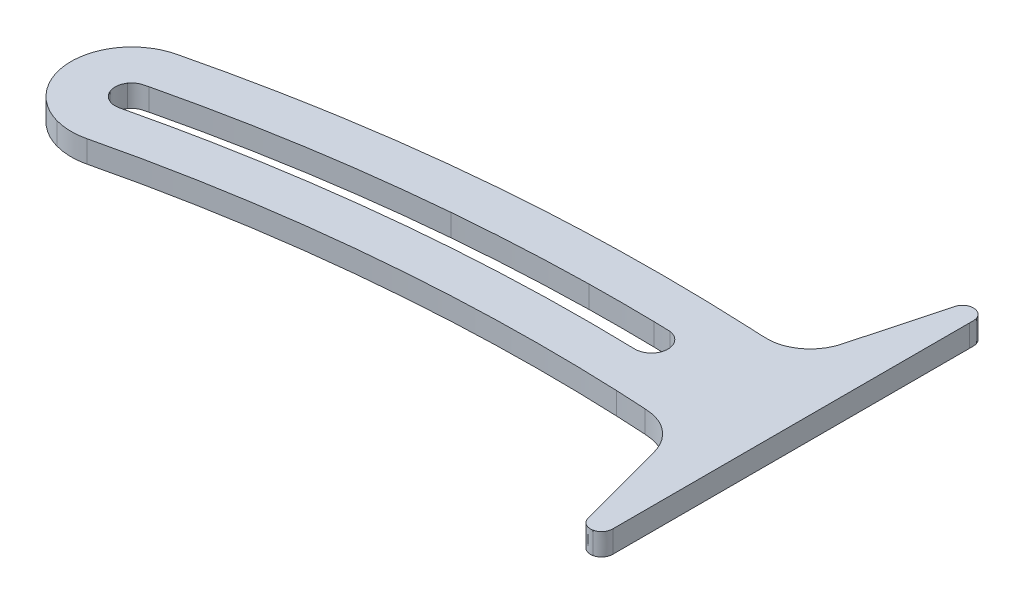
SolidWorks part; units mm, degrees
ref_plane "Front Plane" through (0, 0, 0) normal (0, 0, 1) x (1, 0, 0)
ref_plane "Top Plane" through (0, 0, 0) normal (0, 1, 0) x (1, 0, 0)
ref_plane "Right Plane" through (0, 0, 0) normal (1, 0, 0) x (0, 0, -1)
sketch "Imported Profile" plane through (0, 0, 0) normal (0, 1, 0) x (1, 0, 0)
  spline S0 degree 3 poles (12.8991, 25.236) (15.9171, 24.4093) (18.7007, 24.3473) (21.7531, 25.0501) knots 0 0 0 0 1 1 1 1
  spline S1 degree 3 poles (21.7531, 25.0501) (67.2422, 35.9573) (114.0335, 40.4773) (160.7696, 38.4929) knots 0 0 0 0 1 1 1 1
  spline S2 degree 3 poles (160.7696, 38.4929) (163.6635, 38.3689) (166.5574, 38.2174) (169.4444, 38.0449) knots 0 0 0 0 1 1 1 1
  spline S3 degree 3 poles (169.4444, 38.0449) (172.5863, 37.8589) (175.1081, 37.0734) (177.5541, 34.9719) knots 0 0 0 0 1 1 1 1
  spline S4 degree 3 poles (177.5541, 34.9719) (178.7254, 33.9728) (179.6419, 32.8428) (180.3929, 31.4993) knots 0 0 0 0 1 1 1 1
  spline S5 degree 3 poles (180.3929, 31.4993) (181.1026, 30.2177) (181.4953, 28.8603) (181.8674, 27.4685) knots 0 0 0 0 1 1 1 1
  spline S6 degree 3 poles (181.8674, 27.4685) (182.6184, 24.6642) (183.3694, 21.8599) (184.1205, 19.0625) knots 0 0 0 0 1 1 1 1
  spline S7 degree 3 poles (184.1205, 19.0625) (184.8715, 16.2582) (185.6225, 13.4539) (186.3735, 10.6495) knots 0 0 0 0 1 1 1 1
  spline S8 degree 3 poles (186.3735, 10.6495) (186.7457, 9.2508) (187.1246, 7.8521) (187.4967, 6.4465) knots 0 0 0 0 1 1 1 1
  spline S9 degree 3 poles (187.4967, 6.4465) (187.6827, 5.7506) (187.8756, 5.0478) (188.0617, 4.345) knots 0 0 0 0 1 1 1 1
  spline S10 degree 3 poles (188.0617, 4.345) (188.2477, 3.6491) (188.3786, 2.9463) (188.6335, 2.2642) knots 0 0 0 0 1 1 1 1
  spline S11 degree 3 poles (188.6335, 2.2642) (189.1847, 0.8172) (190.7006, -0.0165) (192.2233, 0.2798) knots 0 0 0 0 1 1 1 1
  spline S12 degree 3 poles (192.2233, 0.2798) (193.7874, 0.5968) (194.7796, 1.9335) (194.7796, 3.4975) knots 0 0 0 0 1 1 1 1
  spline S13 degree 3 poles (194.7796, 3.4975) (194.7796, 6.3983) (194.7796, 9.2991) (194.7796, 12.1998) knots 0 0 0 0 1 1 1 1
  spline S14 degree 3 poles (194.7796, 12.1998) (194.7796, 35.5507) (194.7796, 58.9084) (194.7796, 82.2593) knots 0 0 0 0 1 1 1 1
  spline S15 degree 3 poles (194.7796, 82.2593) (194.7796, 88.0608) (194.7796, 93.8624) (194.7796, 99.6708) knots 0 0 0 0 1 1 1 1
  spline S16 degree 3 poles (194.7796, 99.6708) (194.7796, 101.1178) (194.7796, 102.5716) (194.7796, 104.0185) knots 0 0 0 0 1 1 1 1
  spline S17 degree 3 poles (194.7796, 104.0185) (194.7796, 104.742) (194.7796, 105.4724) (194.7796, 106.1958) knots 0 0 0 0 1 1 1 1
  spline S18 degree 3 poles (194.7796, 106.1958) (194.7796, 106.9193) (194.8485, 107.6152) (194.6072, 108.3387) knots 0 0 0 0 1 1 1 1
  spline S19 degree 3 poles (194.6072, 108.3387) (194.1043, 109.7994) (192.6229, 110.6882) (191.0932, 110.4402) knots 0 0 0 0 1 1 1 1
  spline S20 degree 3 poles (191.0932, 110.4402) (190.2595, 110.3027) (189.6807, 109.9717) (189.1433, 109.3171) knots 0 0 0 0 1 1 1 1
  spline S21 degree 3 poles (189.1433, 109.3171) (188.6541, 108.7176) (188.5094, 108.0424) (188.3234, 107.3327) knots 0 0 0 0 1 1 1 1
  spline S22 degree 3 poles (188.3234, 107.3327) (186.8213, 101.731) (185.3193, 96.1292) (183.8172, 90.5206) knots 0 0 0 0 1 1 1 1
  spline S23 degree 3 poles (183.8172, 90.5206) (183.0662, 87.7232) (182.3909, 84.912) (181.5641, 82.1353) knots 0 0 0 0 1 1 1 1
  spline S24 degree 3 poles (181.5641, 82.1353) (180.7097, 79.2483) (178.8563, 76.7678) (176.3413, 75.121) knots 0 0 0 0 1 1 1 1
  spline S25 degree 3 poles (176.3413, 75.121) (172.2486, 72.4477) (169.1411, 73.0678) (164.7796, 73.2676) knots 0 0 0 0 1 1 1 1
  spline S26 degree 3 poles (164.7796, 73.2676) (145.3906, 74.1909) (126.0843, 74.1289) (106.7022, 73.0126) knots 0 0 0 0 1 1 1 1
  spline S27 degree 3 poles (106.7022, 73.0126) (83.2893, 71.6621) (60.2485, 68.6924) (37.2422, 64.1724) knots 0 0 0 0 1 1 1 1
  spline S28 degree 3 poles (37.2422, 64.1724) (29.3115, 62.6153) (21.4154, 60.9065) (13.5537, 58.9979) knots 0 0 0 0 1 1 1 1
  spline S29 degree 3 poles (13.5537, 58.9979) (13.4434, 58.9679) (13.3332, 58.9429) (13.2298, 58.9154) knots 0 0 0 0 1 1 1 1
  spline S30 degree 3 poles (13.2298, 58.9154) (13.0093, 58.8604) (12.7889, 58.7984) (12.5753, 58.7294) knots 0 0 0 0 1 1 1 1
  spline S31 degree 3 poles (12.5753, 58.7294) (12.1274, 58.5914) (11.6933, 58.4469) (11.2661, 58.2744) knots 0 0 0 0 1 1 1 1
  spline S32 degree 3 poles (11.2661, 58.2744) (10.3773, 57.9229) (9.5298, 57.5027) (8.7099, 57.0135) knots 0 0 0 0 1 1 1 1
  spline S33 degree 3 poles (8.7099, 57.0135) (6.9735, 55.9731) (5.5197, 54.726) (4.2313, 53.1688) knots 0 0 0 0 1 1 1 1
  spline S34 degree 3 poles (4.2313, 53.1688) (1.7439, 50.1716) (0.3383, 46.4302) (0.2281, 42.5373) knots 0 0 0 0 1 1 1 1
  spline S35 degree 3 poles (0.2281, 42.5373) (-0.0062, 34.5515) (5.2166, 27.4271) (12.8991, 25.236) knots 0 0 0 0 1 1 1 1
  spline S36 degree 3 poles (153.0044, 51.4685) (156.4908, 51.3706) (158.8886, 54.9191) (157.5036, 58.1161) knots 0 0 0 0 1 1 1 1
  spline S37 degree 3 poles (157.5036, 58.1161) (156.8353, 59.6595) (155.409, 60.7344) (153.7416, 60.948) knots 0 0 0 0 1 1 1 1
  spline S38 degree 3 poles (153.7416, 60.948) (153.2937, 61.01) (149.5386, 61.072) (149.0907, 61.079) knots 0 0 0 0 1 1 1 1
  spline S39 degree 3 poles (149.0907, 61.079) (142.8482, 61.196) (136.5988, 61.203) (130.3494, 61.094) knots 0 0 0 0 1 1 1 1
  spline S40 degree 3 poles (130.3494, 61.094) (117.7059, 60.8805) (105.1106, 60.212) (92.5154, 59.0889) knots 0 0 0 0 1 1 1 1
  spline S41 degree 3 poles (92.5154, 59.0889) (67.2422, 56.8358) (42.4581, 52.8051) (17.7706, 46.9484) knots 0 0 0 0 1 1 1 1
  spline S42 degree 3 poles (17.7706, 46.9484) (16.1652, 46.5694) (14.7734, 46.2387) (13.7329, 44.6953) knots 0 0 0 0 1 1 1 1
  spline S43 degree 3 poles (13.7329, 44.6953) (12.8234, 43.3517) (12.6649, 41.6499) (13.3057, 40.1547) knots 0 0 0 0 1 1 1 1
  spline S44 degree 3 poles (13.3057, 40.1547) (13.9672, 38.6044) (15.4072, 37.5226) (17.0816, 37.309) knots 0 0 0 0 1 1 1 1
  spline S45 degree 3 poles (17.0816, 37.309) (17.8808, 37.2055) (18.6112, 37.359) (19.3691, 37.5365) knots 0 0 0 0 1 1 1 1
  spline S46 degree 3 poles (19.3691, 37.5365) (20.127, 37.7225) (20.8849, 37.9015) (21.6429, 38.074) knots 0 0 0 0 1 1 1 1
  spline S47 degree 3 poles (21.6429, 38.074) (27.7269, 39.5002) (33.8316, 40.8094) (39.9708, 42.0151) knots 0 0 0 0 1 1 1 1
  spline S48 degree 3 poles (39.9708, 42.0151) (52.38, 44.4405) (64.8375, 46.4111) (77.3914, 47.9269) knots 0 0 0 0 1 1 1 1
  spline S49 degree 3 poles (77.3914, 47.9269) (102.5751, 50.9655) (127.6485, 52.1368) (153.0044, 51.4685) knots 0 0 0 0 1 1 1 1
extrude "Boss-Extrude1" add sketch "Imported Profile" along normal blind 6.35 contours S27 S28 S29 S30 S31 S32 S33 S34 S35 S0 S1 S2 S3 S4 S5 S6 S7 S8 S9 S10 S11 S12 S13 S14 S15 S16 S17 S18 S19 S20 S21 S22 S23 S24 S25 S26
sketch "Sketch1" plane through (0, 6.35, 0) normal (0, 1, 0) x (1, 0, 0)
  line L0 (191.616, 107.3087) -> (191.616, 3.4975) construction
  line L1 (194.7796, 107.3087) -> (194.7796, 3.4975) construction
  line L2 (188.4524, 107.3087) -> (188.4524, 3.4975) construction
  line L5 (194.7796, 12.1998) -> (194.7796, 82.2593) construction
  line L6 (194.7796, 55.4031) -> (171.9196, 55.4031) construction
  arc A0 (194.7796, 107.3087) -> (188.4524, 107.3087) centre (191.616, 107.3087) ccw construction
  arc A1 (188.4524, 3.4975) -> (194.7796, 3.4975) centre (191.616, 3.4975) ccw construction
  spline S0 degree 3 poles (194.6072, 108.3387) (194.1043, 109.7994) (192.6229, 110.6882) (191.0932, 110.4402) knots 0 0 0 0 1 1 1 1 construction
  spline S1 degree 3 poles (192.2233, 0.2798) (193.7874, 0.5968) (194.7796, 1.9335) (194.7796, 3.4975) knots 0 0 0 0 1 1 1 1 construction
  point P2 (191.616, 55.4031)
  dimension "D1" = 22.86
  dimension "D2" = 6.3272
sketch3d "3DSketch1"
  line L0 (171.9196, 6.35, -55.4031) -> (171.9196, 0, -55.4031) construction
sketch "Sketch2" plane through (0, 0, 0) normal (0, -1, 0) x (1, 0, 0)
  line L0 (131.3895, -51.8859) -> (96.6153, -50.1813) construction
  line L1 (114.0024, -51.0336) -> (113.5363, -60.5407) construction
  line L2 (41.428, -42.497) -> (69.6198, -47.1272) construction
  line L3 (55.5239, -44.8121) -> (53.9795, -54.2158) construction
  circle A0 centre (153.1375, -56.2248) radius 4.7582 construction
  circle A1 centre (17.6798, -42.0304) radius 4.7593 construction
  spline S0 degree 3 poles (153.0044, -51.4685) (156.4908, -51.3706) (158.8886, -54.9191) (157.5036, -58.1161) knots 0 0 0 0 1 1 1 1 construction
  spline S2 degree 3 poles (17.0816, -37.309) (17.8808, -37.2055) (18.6112, -37.359) (19.3691, -37.5365) knots 0 0 0 0 1 1 1 1 construction
  spline S3 degree 3 poles (13.7329, -44.6953) (12.8234, -43.3517) (12.6649, -41.6499) (13.3057, -40.1547) knots 0 0 0 0 1 1 1 1 construction
  spline S4 degree 3 poles (153.1375, -56.2248) (107.1548, -57.4301) (62.0117, -52.6466) (17.6798, -42.0304) knots 0 0 0 0 1 1 1 1
  spline S7 degree 3 poles (77.3914, -47.9269) (102.5751, -50.9655) (127.6485, -52.1368) (153.0044, -51.4685) knots 0 0 0 0 1 1 1 1 construction
  spline S8 degree 3 poles (130.3494, -61.094) (117.7059, -60.8805) (105.1106, -60.212) (92.5154, -59.0889) knots 0 0 0 0 1 1 1 1 construction
  spline S10 degree 3 poles (92.5154, -59.0889) (67.2422, -56.8358) (42.4581, -52.8051) (17.7706, -46.9484) knots 0 0 0 0 1 1 1 1 construction
  spline S11 degree 3 poles (39.9708, -42.0151) (52.38, -44.4405) (64.8375, -46.4111) (77.3914, -47.9269) knots 0 0 0 0 1 1 1 1 construction
  point P16 (114.0024, -51.0336)
  point P18 (113.7694, -55.7872)
  point P26 (55.5239, -44.8121)
  point P38 (54.7517, -49.5139)
  dimension "D1" = 39.002
  dimension "D2" = 33.8811
